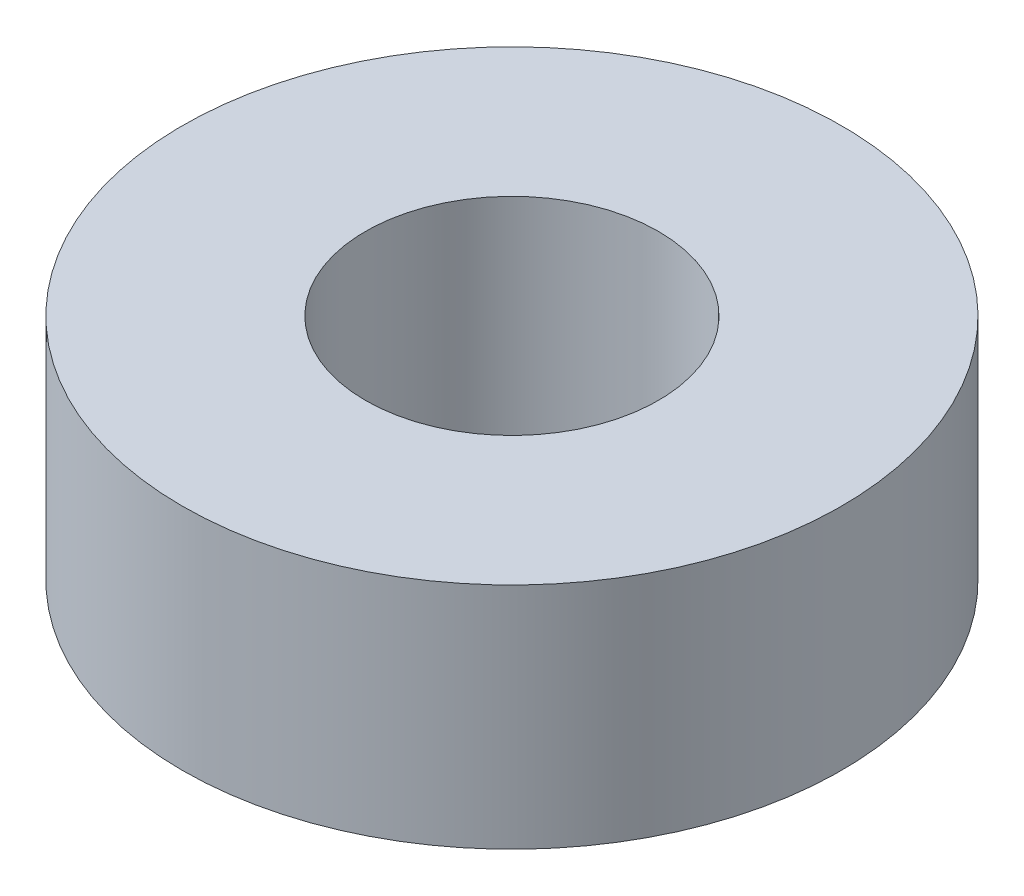
SolidWorks part; units mm, degrees
ref_plane "前视基准面" through (0, 0, 0) normal (0, 0, 1) x (1, 0, 0)
ref_plane "上视基准面" through (0, 0, 0) normal (0, 1, 0) x (1, 0, 0)
ref_plane "右视基准面" through (0, 0, 0) normal (1, 0, 0) x (0, 0, -1)
sketch "草图1" plane through (0, 0, 0) normal (0, 1, 0) x (1, 0, 0)
  circle A0 centre (0, 0) radius 1.6
  circle A1 centre (0, 0) radius 3.6
  dimension "D1" = 3.2
  dimension "D2" = 2
extrude "凸台-拉伸1" add sketch "草图1" along normal blind 2.5
